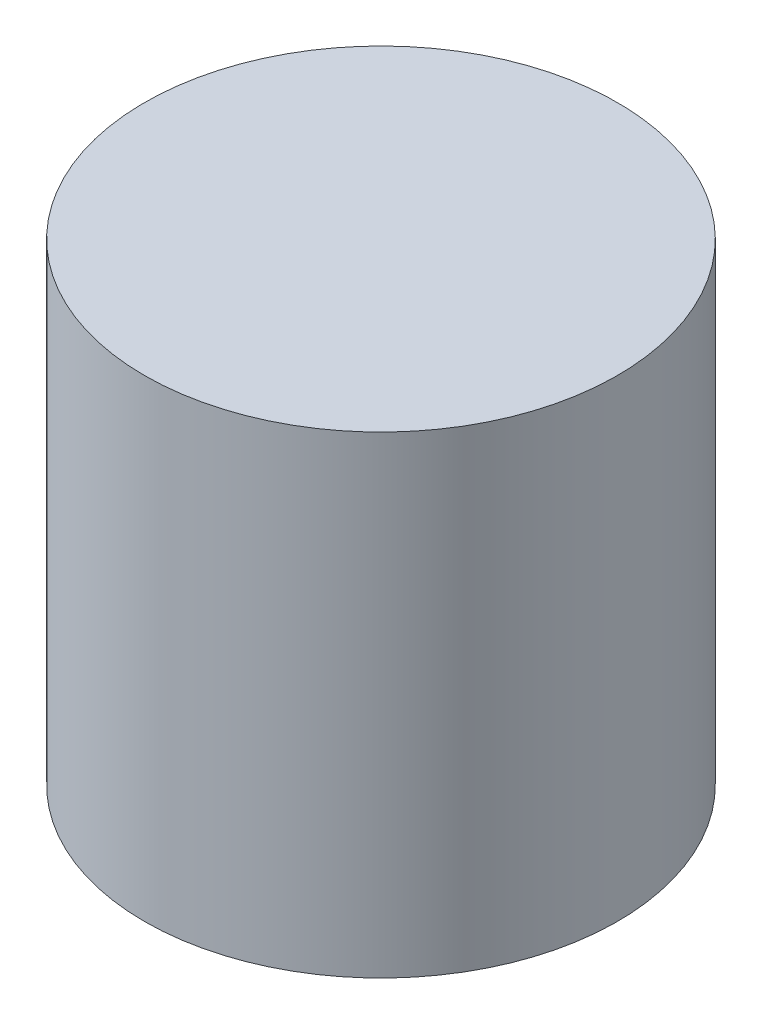
SolidWorks part; units mm, degrees
ref_plane "Plan de face" through (0, 0, 0) normal (0, 0, 1) x (1, 0, 0)
ref_plane "Plan de dessus" through (0, 0, 0) normal (0, 1, 0) x (1, 0, 0)
ref_plane "Plan de droite" through (0, 0, 0) normal (1, 0, 0) x (0, 0, -1)
sketch "Esquisse1" plane through (0, 0, 0) normal (0, 1, 0) x (1, 0, 0)
  circle A0 centre (0, 0) radius 3
  dimension "D1" = 6
extrude "Boss.-Extru.1" add sketch "Esquisse1" along normal blind 6
